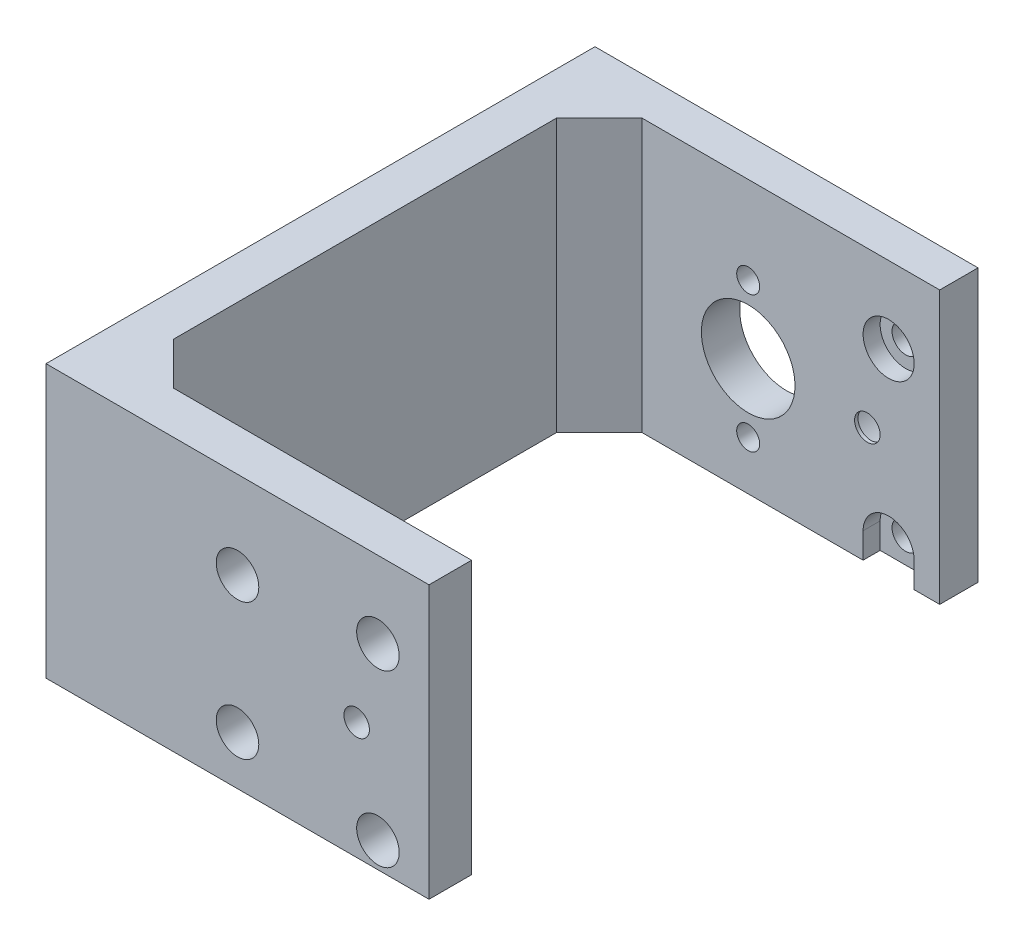
SolidWorks part; units mm, degrees
ref_plane "Front Plane" through (0, 0, 0) normal (0, 0, 1) x (1, 0, 0)
ref_plane "Top Plane" through (0, 0, 0) normal (0, 1, 0) x (1, 0, 0)
ref_plane "Right Plane" through (0, 0, 0) normal (1, 0, 0) x (0, 0, -1)
sketch "Sketch1" plane through (0, 0, 0) normal (0, 0, 1) x (1, 0, 0)
  line L0 (32.5, -4) -> (-1, -4) construction
  line L1 (0, 27.5) -> (32.5, 27.5)
  line L3 (0, 27.5) -> (0, 0) construction
  line L4 (32.5, 27.5) -> (32.5, 0)
  line L5 (0, 0) -> (32.5, 0)
  line L6 (32.5, 0) -> (32.5, -4) construction
  line L7 (24, -5) -> (29.866, -5) construction
  line L8 (0, 27.5) -> (-12.5, 27.5)
  line L9 (-12.5, 27.5) -> (-12.5, 0)
  line L10 (-12.5, 0) -> (0, 0)
  circle A0 centre (10, 13.75) radius 5.5
  circle A1 centre (24, 13.75) radius 4.45
  circle A4 centre (24, 13.75) radius 18.75 construction
  dimension "D1" = 11
  dimension "D2" = 8.9
  dimension "D3" = 14
  dimension "D5" = 1
  dimension "D10" = 37.5
  dimension "D8" = 22.5
  dimension "D4" = 22.5
  dimension "D6" = 27.5
  dimension "D7" = 4
  dimension "D9" = 10
extrude "Boss-Extrude1" add sketch "Sketch1" along normal blind 4.5
sketch "Sketch2" plane through (0, 0, 4.5) normal (0, 0, 1) x (1, 0, 0)
  circle A0 centre (24, 13.75) radius 4.45 construction
  circle A1 centre (24, 13.75) radius 4.45
  circle A2 centre (24, 13.75) radius 1.5
  dimension "D1" = 3
extrude "Boss-Extrude2" add sketch "Sketch2" against normal blind 0.4
sketch "Sketch3" plane through (0, 0, 4.5) normal (0, 0, 1) x (1, 0, 0)
  line L0 (10, 0) -> (10, 27.5) construction
  line L1 (-12.5, 0) -> (32.5, 0) construction
  line L2 (32.5, 27.5) -> (-12.5, 27.5) construction
  circle A12 centre (26.5, 23) radius 1.6
  circle A13 centre (26.5, 3) radius 1.6
  circle A14 centre (-6.5, 23) radius 1.6 construction
  circle A15 centre (-6.5, 3) radius 1.6 construction
  circle A16 centre (10, 13.75) radius 5.5 construction
  dimension "D1" = 3.2
  dimension "D2" = 3.2
  dimension "D3" = 20
  dimension "D6" = 3.2
  dimension "D7" = 3.2
  dimension "D8" = 33
  dimension "D4" = 16.5
  dimension "D5" = 3
extrude "Cut-Extrude1" cut sketch "Sketch3" against normal blind 10
sketch "Sketch4" plane through (0, 0, 4.5) normal (0, 0, 1) x (1, 0, 0)
  line L0 (2, 13.75) -> (18, 13.75) construction
  line L1 (10, 21.75) -> (10, 5.75) construction
  circle A0 centre (2, 13.75) radius 1.35 construction
  circle A1 centre (18, 13.75) radius 1.35 construction
  circle A2 centre (10, 21.75) radius 1.35
  circle A3 centre (10, 5.75) radius 1.35
  point P4 (10, 13.75)
  point P9 (10, 13.75)
  dimension "D1" = 2.7
  dimension "D2" = 2.7
  dimension "D3" = 16
extrude "Cut-Extrude2" cut sketch "Sketch4" against normal blind 10
sketch "Sketch5" plane through (0, 0, 4.5) normal (0, 0, 1) x (1, 0, 0)
  line L1 (-12.5, 27.5) -> (32.5, 27.5)
  line L2 (-12.5, 27.5) -> (-12.5, 32)
  line L3 (-12.5, 32) -> (32.5, 32)
  line L4 (32.5, 27.5) -> (32.5, 32)
  line L5 (10, 32) -> (10, 27.5) construction
  line L6 (-12.5, 29.75) -> (32.5, 29.75) construction
  point P180 (10, 29.75)
  dimension "D1" = 4.5
extrude "Boss-Extrude3" add sketch "Sketch5" against normal up to vertex (4.5 mm away)
fillet "Fillet1" [suppressed] radius 2
sketch "Sketch6" plane through (0, 0, 4.5) normal (0, 0, 1) x (1, 0, 0)
  line L0 (23.5, 3) -> (23.5, 0)
  line L1 (-12.5, 0) -> (32.5, 0) construction
  line L2 (23.5, 0) -> (29.5, 0)
  line L3 (29.5, 0) -> (29.5, 3)
  arc A5 (29.5, 3) -> (23.5, 3) centre (26.5, 3) ccw
  circle A6 centre (26.5, 23) radius 3
  dimension "D3" = 6
  dimension "D4" = 6
extrude "Cut-Extrude4" cut sketch "Sketch6" against normal blind 2
sketch "Sketch7" plane through (0, 0, 4.5) normal (0, 0, 1) x (1, 0, 0)
  line L0 (32.5, 32) -> (-12.5, 32) construction
  line L1 (-12.5, 0) -> (-7.5, 0)
  line L2 (-12.5, 0) -> (-12.5, 32)
  line L3 (-12.5, 32) -> (-7.5, 32)
  line L4 (-7.5, 0) -> (-7.5, 32)
  line L5 (-10, 32) -> (-10, 0) construction
  line L6 (-12.5, 16) -> (-7.5, 16) construction
  point P4 (-7.5, 32)
  point P96 (-10, 16)
  dimension "D1" = 5
extrude "Boss-Extrude4" add sketch "Sketch7" along normal blind 60
sketch "Sketch8" plane through (-7.5, 0, 0) normal (1, 0, 0) x (0, 0, -1)
  line L0 (-64.5, 32) -> (-4.5, 32) construction
  line L1 (-64.5, 0) -> (-59.5, 0)
  line L2 (-64.5, 0) -> (-64.5, 32)
  line L3 (-64.5, 32) -> (-59.5, 32)
  line L4 (-59.5, 0) -> (-59.5, 32)
  line L5 (-62, 32) -> (-62, 0) construction
  line L6 (-64.5, 16) -> (-59.5, 16) construction
  point P72 (-62, 16)
  dimension "D1" = 5
extrude "Boss-Extrude5" add sketch "Sketch8" along normal up to vertex (40 mm away)
sketch "Sketch11" plane through (0, 0, 64.5) normal (0, 0, 1) x (1, 0, 0)
  circle A0 centre (26.5, 3) radius 1.6 construction
  circle A1 centre (10, 5.75) radius 1.35 construction
  circle A2 centre (10, 21.75) radius 1.35 construction
  circle A3 centre (26.5, 23) radius 1.6 construction
  circle A4 centre (26.5, 3) radius 1.6 construction
  circle A5 centre (10, 5.75) radius 1.35 construction
  circle A6 centre (10, 21.75) radius 1.35 construction
  circle A7 centre (26.5, 23) radius 1.6 construction
  circle A8 centre (10, 21.75) radius 2.5
  circle A9 centre (26.5, 23) radius 2.5
  circle A10 centre (26.5, 3) radius 2.5
  circle A11 centre (10, 5.75) radius 2.5
  circle A12 centre (24, 13.75) radius 1.5 construction
  circle A13 centre (24, 13.75) radius 1.5
  dimension "D1" = 5
  dimension "D2" = 5
  dimension "D3" = 5
  dimension "D4" = 5
extrude "Cut-Extrude5" cut sketch "Sketch11" against normal up to vertex (5 mm away)
chamfer "Chamfer1" distance 5 angle 45 2 edges at (-7.5, 16, 59.5) (-7.5, 16, 4.5)
